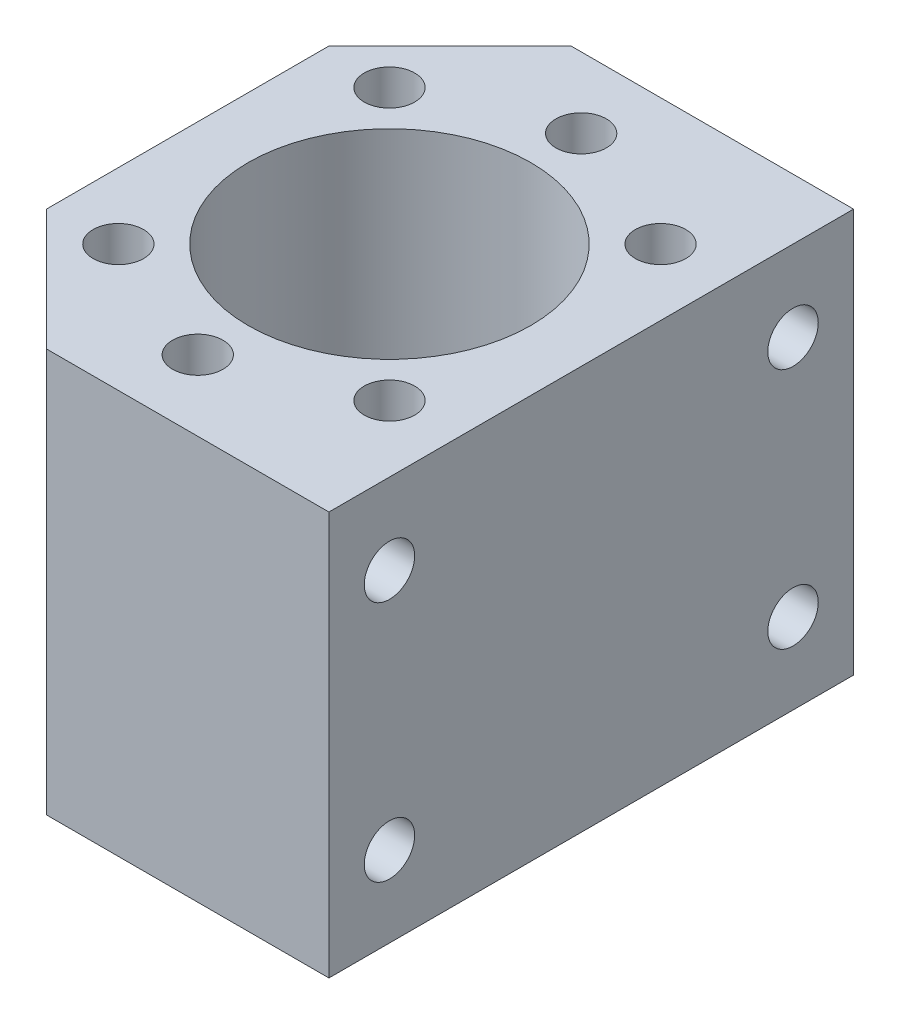
SolidWorks part; units mm, degrees
material "1060 Alloy"
ref_plane "Front Plane" through (0, 0, 0) normal (0, 0, 1) x (1, 0, 0)
ref_plane "Top Plane" through (0, 0, 0) normal (0, 1, 0) x (1, 0, 0)
ref_plane "Right Plane" through (0, 0, 0) normal (1, 0, 0) x (0, 0, -1)
sketch "Sketch2" plane through (0, 0, 0) normal (0, 1, 0) x (1, 0, 0)
  line L0 (0, 0) -> (40, 0)
  line L1 (40, 0) -> (40, -52)
  line L2 (40, -52) -> (0, -52)
  line L3 (0, -52) -> (0, 0)
extrude "Boss-Extrude1" add sketch "Sketch2" along normal blind 40
sketch "Sketch3" plane through (0, 40, 0) normal (0, 1, 0) x (1, 0, 0)
  line L0 (40, -26) -> (20, -26) construction
  line L1 (40, -52) -> (40, 0) construction
  circle A0 centre (20, -26) radius 14
  dimension "D1" = 28
extrude "Cut-Extrude1" cut sketch "Sketch3" against normal blind 40
sketch "Sketch4" plane through (0, 40, 0) normal (0, 1, 0) x (1, 0, 0)
  line L0 (0, -52) -> (12, -52)
  line L1 (0, -52) -> (40, -52) construction
  line L2 (0, 0) -> (12, 0)
  line L3 (0, -52) -> (0, -40)
  line L4 (0, 0) -> (0, -52) construction
  line L5 (0, -40) -> (12, -52)
  line L6 (40, 0) -> (0, 0) construction
  line L7 (0, 0) -> (0, -12)
  line L8 (0, -12) -> (12, 0)
extrude "Cut-Extrude2" cut sketch "Sketch4" against normal blind 40
sketch "Sketch5" plane through (0, 40, 0) normal (0, 1, 0) x (1, 0, 0)
  line L0 (20, -7) -> (20, -45) construction
  line L1 (20, -26) -> (33.435, -12.565) construction
  line L2 (33.435, -12.565) -> (6.565, -12.565) construction
  line L3 (6.565, -12.565) -> (6.565, -39.435) construction
  line L4 (6.565, -39.435) -> (33.435, -39.435) construction
  line L5 (33.435, -39.435) -> (33.435, -12.565) construction
  circle A0 centre (20, -26) radius 19 construction
  circle A1 centre (20, -7) radius 2.5
  circle A2 centre (20, -45) radius 2.5
  circle A3 centre (33.435, -39.435) radius 2.5
  circle A4 centre (33.435, -12.565) radius 2.5
  circle A5 centre (6.565, -12.565) radius 2.5
  circle A6 centre (6.565, -39.435) radius 2.5
  dimension "D1" = 38
  dimension "D2" = 5
  dimension "D3" = 5
  dimension "D4" = 5
  dimension "D5" = 5
  dimension "D6" = 5
  dimension "D7" = 5
extrude "Cut-Extrude3" cut sketch "Sketch5" against normal blind 20
sketch "Sketch6" plane through (40, 0, 0) normal (1, 0, 0) x (0, 0, -1)
  line L0 (-52, 40) -> (-52, 32) construction
  line L1 (-52, 40) -> (-52, 0) construction
  line L2 (-52, 32) -> (-46, 32) construction
  line L3 (-46, 32) -> (-46, 8) construction
  line L4 (-46, 8) -> (-6, 8) construction
  line L5 (-6, 8) -> (-6, 32) construction
  circle A0 centre (-46, 32) radius 2.5
  circle A1 centre (-46, 8) radius 2.5
  circle A2 centre (-6, 8) radius 2.5
  circle A3 centre (-6, 32) radius 2.5
  dimension "D1" = 5
  dimension "D2" = 5
  dimension "D3" = 5
  dimension "D4" = 5
extrude "Cut-Extrude4" cut sketch "Sketch6" against normal blind 15
